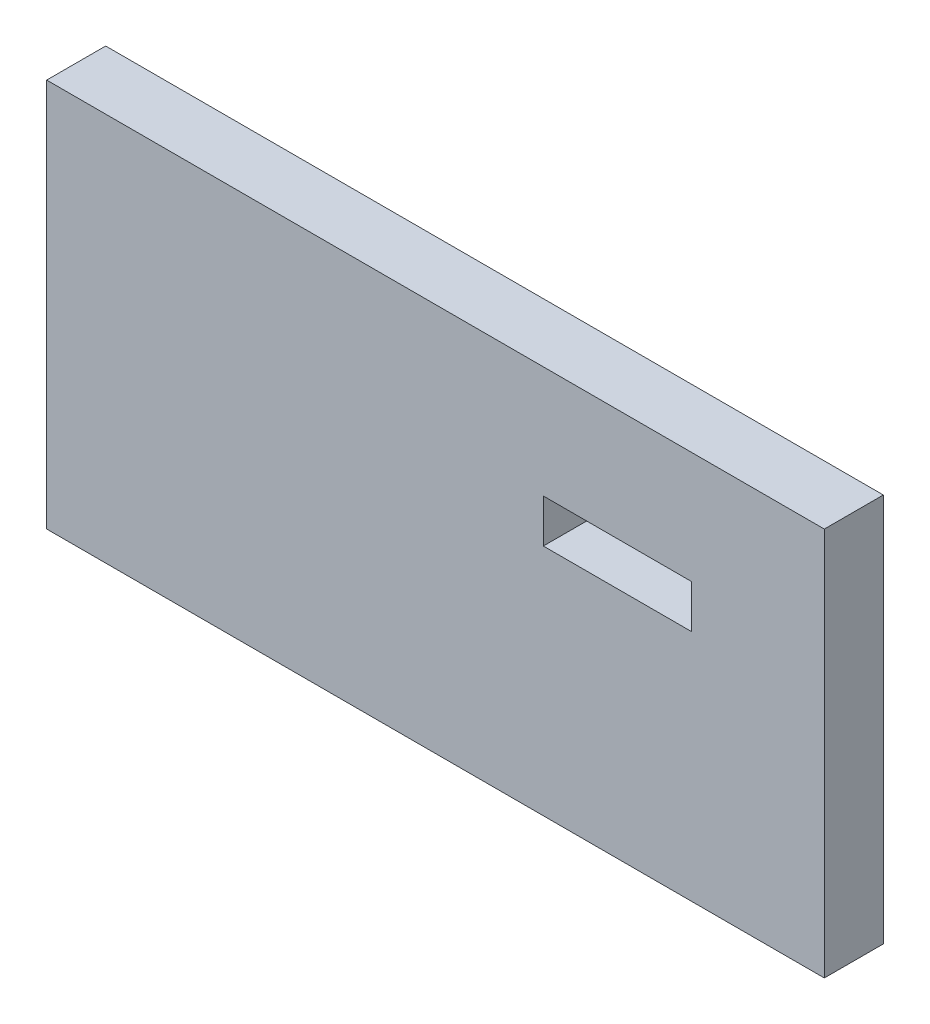
SolidWorks part; units mm, degrees
ref_plane "Front Plane" through (0, 0, 0) normal (0, 0, 1) x (1, 0, 0)
ref_plane "Top Plane" through (0, 0, 0) normal (0, 1, 0) x (1, 0, 0)
ref_plane "Right Plane" through (0, 0, 0) normal (1, 0, 0) x (0, 0, -1)
sketch "Sketch1" plane through (0, 0, 0) normal (0, 0, 1) x (1, 0, 0)
  line L1 (0, 0) -> (131.7823, 0)
  line L2 (0, 0) -> (0, 65.8912)
  line L3 (0, 65.8912) -> (131.7823, 65.8912)
  line L4 (131.7823, 0) -> (131.7823, 65.8912)
  line L5 (84.1666, 46.9356) -> (109.2895, 46.9356)
  line L6 (84.1666, 46.9356) -> (84.1666, 39.5891)
  line L7 (84.1666, 39.5891) -> (109.2895, 39.5891)
  line L8 (109.2895, 46.9356) -> (109.2895, 39.5891)
extrude "Boss-Extrude1" add sketch "Sketch1" along normal blind 10
sketch "Sketch2" plane through (0, 0, 10) normal (0, 0, 1) x (1, 0, 0)
  circle A0 centre (30.9238, 22.9153) radius 10.8112
